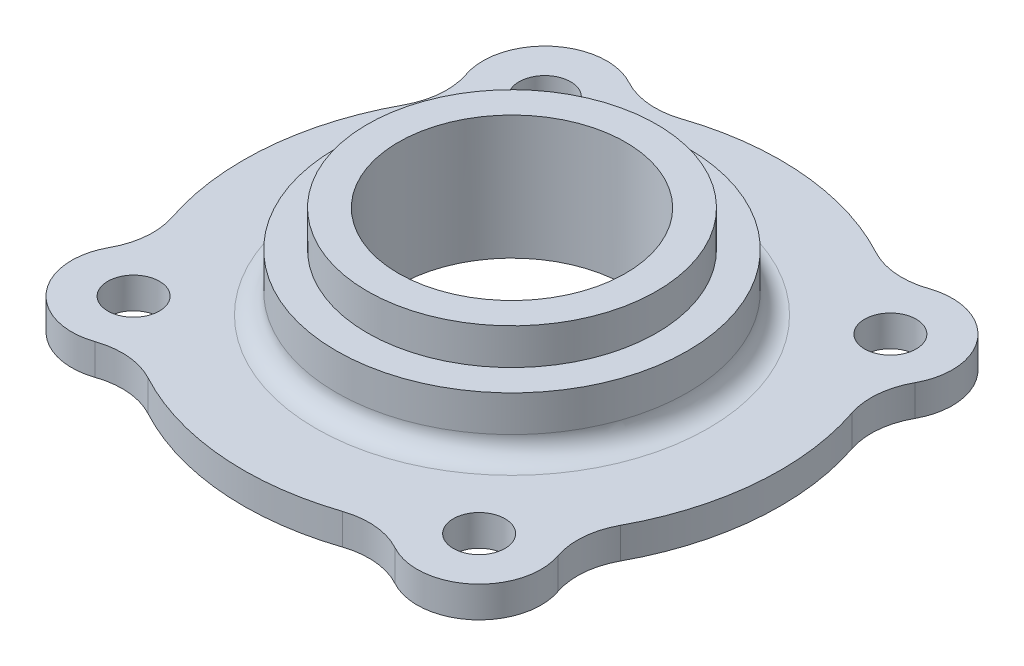
SolidWorks part; units mm, degrees
ref_plane "Front Plane" through (0, 0, 0) normal (0, 0, 1) x (1, 0, 0)
ref_plane "Top Plane" through (0, 0, 0) normal (0, 1, 0) x (1, 0, 0)
ref_plane "Right Plane" through (0, 0, 0) normal (1, 0, 0) x (0, 0, -1)
sketch "Sketch1" plane through (0, 0, 0) normal (0, 1, 0) x (1, 0, 0)
  arc A1 (-12.3689, -22.8694) -> (8.2434, -24.6586) centre (0, 0) ccw
  arc A6 (-13.8353, 25.1635) -> (-22.4032, 17.9642) centre (-16.7261, 19.9058) ccw
  arc A7 (-22.8694, 12.3689) -> (-24.6586, -8.2434) centre (0, 0) ccw
  arc A8 (25.1635, 13.8353) -> (17.9642, 22.4032) centre (19.9058, 16.7261) ccw
  arc A9 (12.3689, 22.8694) -> (-8.2434, 24.6586) centre (0, 0) ccw
  arc A10 (13.8353, -25.1635) -> (22.4032, -17.9642) centre (16.7261, -19.9058) ccw
  arc A11 (22.8694, -12.3689) -> (24.6586, 8.2434) centre (0, 0) ccw
  arc A12 (-25.1635, -13.8353) -> (-17.9642, -22.4032) centre (-19.9058, -16.7261) ccw
  arc A13 (-17.9642, -22.4032) -> (-12.3689, -22.8694) centre (-15.699, -29.0266) cw
  arc A14 (8.2434, -24.6586) -> (13.8353, -25.1635) centre (10.4627, -31.2975) cw
  arc A15 (22.4032, -17.9642) -> (22.8694, -12.3689) centre (29.0266, -15.699) cw
  arc A16 (24.6586, 8.2434) -> (25.1635, 13.8353) centre (31.2975, 10.4627) cw
  arc A17 (17.9642, 22.4032) -> (12.3689, 22.8694) centre (15.699, 29.0266) cw
  arc A18 (-13.8353, 25.1635) -> (-8.2434, 24.6586) centre (-10.4627, 31.2975) ccw
  arc A19 (-22.4032, 17.9642) -> (-22.8694, 12.3689) centre (-29.0266, 15.699) cw
  arc A20 (-24.6586, -8.2434) -> (-25.1635, -13.8353) centre (-31.2975, -10.4627) cw
  point P16 (0, 0)
  point P30 (20.8436, -15.5416)
  point P35 (15.5416, 20.8436)
  point P40 (-20.8436, 15.5416)
  point P43 (-23.2098, -11.7177)
extrude "Boss-Extrude1" add sketch "Sketch1" against normal blind 3 contours A1 A14 A10 A15 A11 A16 A8 A17 A9 A18 A6 A19 A7 A20 A12 A13
sketch "Sketch2" plane through (0, 0, 0) normal (0, 1, 0) x (1, 0, 0)
  circle A0 centre (0, 0) radius 17
  dimension "D1" = 34
extrude "Boss-Extrude2" add sketch "Sketch2" along normal blind 5.5 contours A0
sketch "Sketch5" plane through (0, 5.5, 0) normal (0, 1, 0) x (1, 0, 0)
  circle A0 centre (0, 0) radius 14
  dimension "D1" = 28
extrude "Boss-Extrude3" add sketch "Sketch5" along normal blind 3.5 contours A0
sketch "Sketch6" plane through (0, 9, 0) normal (0, 1, 0) x (1, 0, 0)
  circle A0 centre (0, 0) radius 11
  dimension "D1" = 22
extrude "Cut-Extrude1" cut sketch "Sketch6" against normal blind 44.5 contours A0
sketch "Sketch7" plane through (0, 0, 0) normal (0, 1, 0) x (1, 0, 0)
  circle A0 centre (-16.7261, 19.9058) radius 2.5
  dimension "D1" = 5
extrude "Cut-Extrude2" cut sketch "Sketch7" against normal blind 44.5 contours A0
sketch "Sketch8" plane through (0, 0, 0) normal (0, 1, 0) x (1, 0, 0)
  circle A0 centre (16.7261, -19.9058) radius 2.5
  dimension "D1" = 5
extrude "Cut-Extrude3" cut sketch "Sketch8" against normal blind 44.5
sketch "Sketch9" plane through (0, 0, 0) normal (0, 1, 0) x (1, 0, 0)
  circle A0 centre (-19.9058, -16.7261) radius 2.5
  dimension "D1" = 5
extrude "Cut-Extrude4" cut sketch "Sketch9" against normal blind 44.5
sketch "Sketch10" plane through (0, 0, 0) normal (0, 1, 0) x (1, 0, 0)
  circle A0 centre (19.9058, 16.7261) radius 2.5
  dimension "D1" = 5
extrude "Cut-Extrude5" cut sketch "Sketch10" against normal blind 44.5
fillet "Fillet23" radius 2 1 edges at (0, 0, 17)
